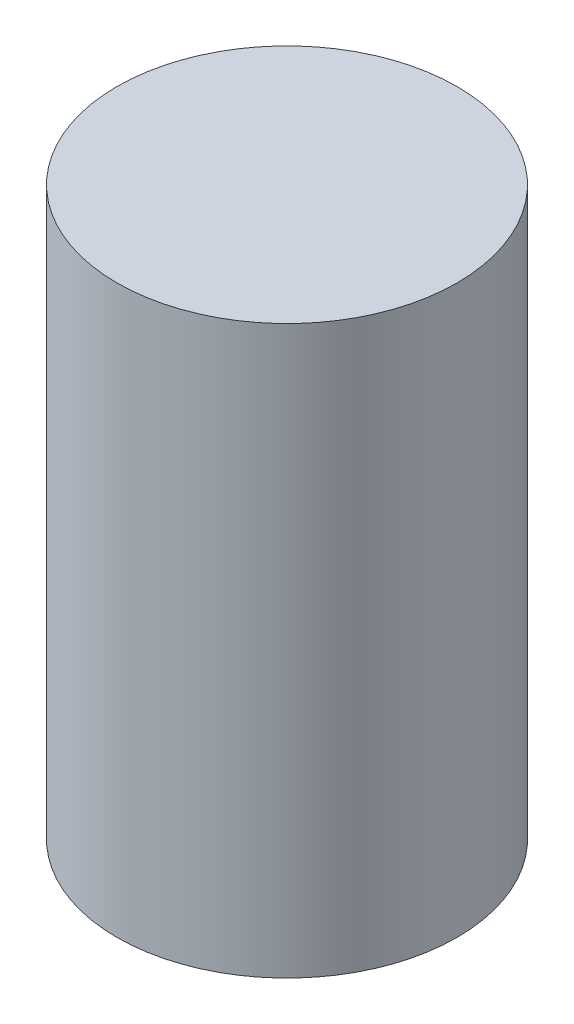
SolidWorks part; units mm, degrees
ref_plane "前视基准面" through (0, 0, 0) normal (0, 0, 1) x (1, 0, 0)
ref_plane "上视基准面" through (0, 0, 0) normal (0, 1, 0) x (1, 0, 0)
ref_plane "右视基准面" through (0, 0, 0) normal (1, 0, 0) x (0, 0, -1)
other "Configuration Table"
sketch "草图1" plane through (0, 0, 0) normal (0, 1, 0) x (1, 0, 0)
  circle A0 centre (0, 0) radius 300
  dimension "D1" = 600
extrude "凸台-拉伸1" add sketch "草图1" along normal blind 1000
